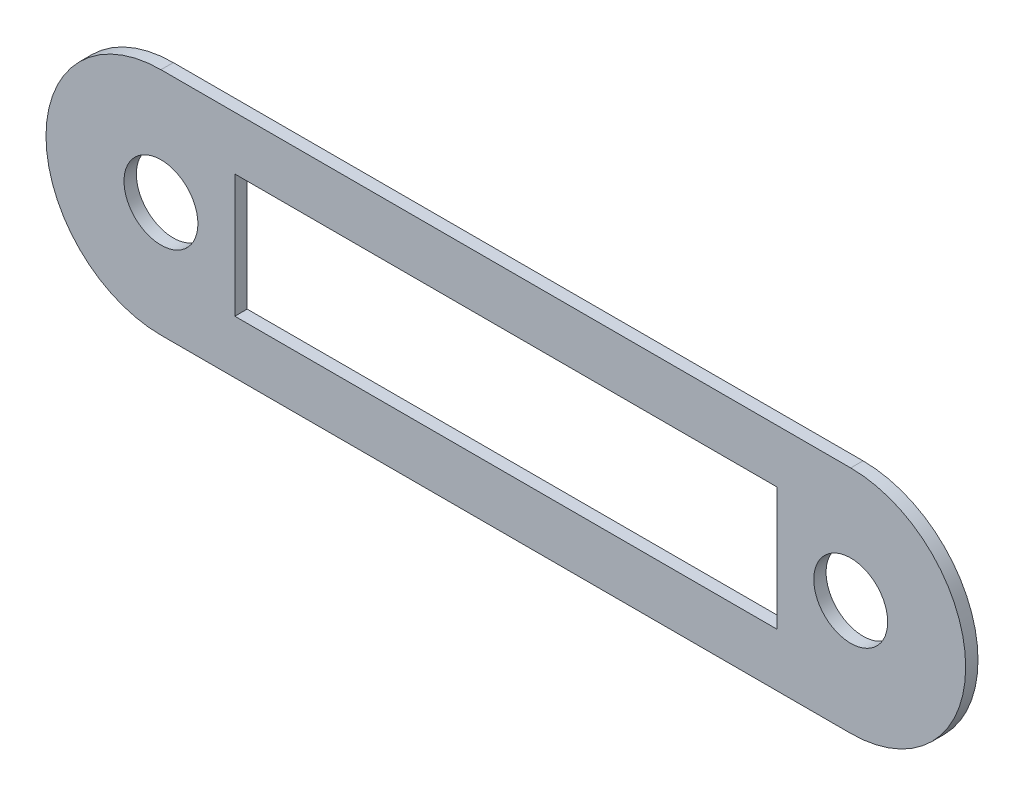
SolidWorks part; units mm, degrees
material "Silicon"
ref_plane "Front" through (0, 0, 0) normal (0, 0, 1) x (1, 0, 0)
ref_plane "Top" through (0, 0, 0) normal (0, 1, 0) x (1, 0, 0)
ref_plane "Right" through (0, 0, 0) normal (1, 0, 0) x (0, 0, -1)
sketch "Sketch1" plane through (0, 0, 0) normal (0, 0, 1) x (1, 0, 0)
  line L0 (0, 0) -> (28, 0) construction
  line L1 (0, 4.6667) -> (28, 4.6667)
  line L2 (0, -4.6667) -> (28, -4.6667)
  arc A0 (0, 4.6667) -> (0, -4.6667) centre (0, 0) ccw
  arc A1 (28, -4.6667) -> (28, 4.6667) centre (28, 0) ccw
  point P3 (14, 0)
  dimension "D1" = 28
extrude "Boss-Extrude1" add sketch "Sketch1" along normal blind 0.5
sketch "Sketch2" plane through (0, 0, 0.5) normal (0, 0, 1) x (1, 0, 0)
  circle A0 centre (0, 0) radius 1.5
extrude "Cut-Extrude1" cut sketch "Sketch2" against normal blind 0.5
sketch "Sketch3" plane through (0, 0, 0.5) normal (0, 0, 1) x (1, 0, 0)
  circle A0 centre (28, 0) radius 1.5
extrude "Cut-Extrude2" cut sketch "Sketch3" against normal blind 0.5
sketch "Sketch4" plane through (0, 0, 0.5) normal (0, 0, 1) x (1, 0, 0)
  line L0 (0, 0) -> (28, 0) construction
  line L2 (25, 2.5) -> (3, 2.5)
  line L3 (25, 2.5) -> (25, -2.5)
  line L4 (25, -2.5) -> (3, -2.5)
  line L5 (3, 2.5) -> (3, -2.5)
  line L6 (25, 2.5) -> (3, -2.5) construction
  line L7 (25, -2.5) -> (3, 2.5) construction
  point P4 (14, 0)
  dimension "D1" = 22
  dimension "D2" = 5
extrude "Cut-Extrude3" cut sketch "Sketch4" against normal blind 0.5 contours L2 L5 L4 L3
